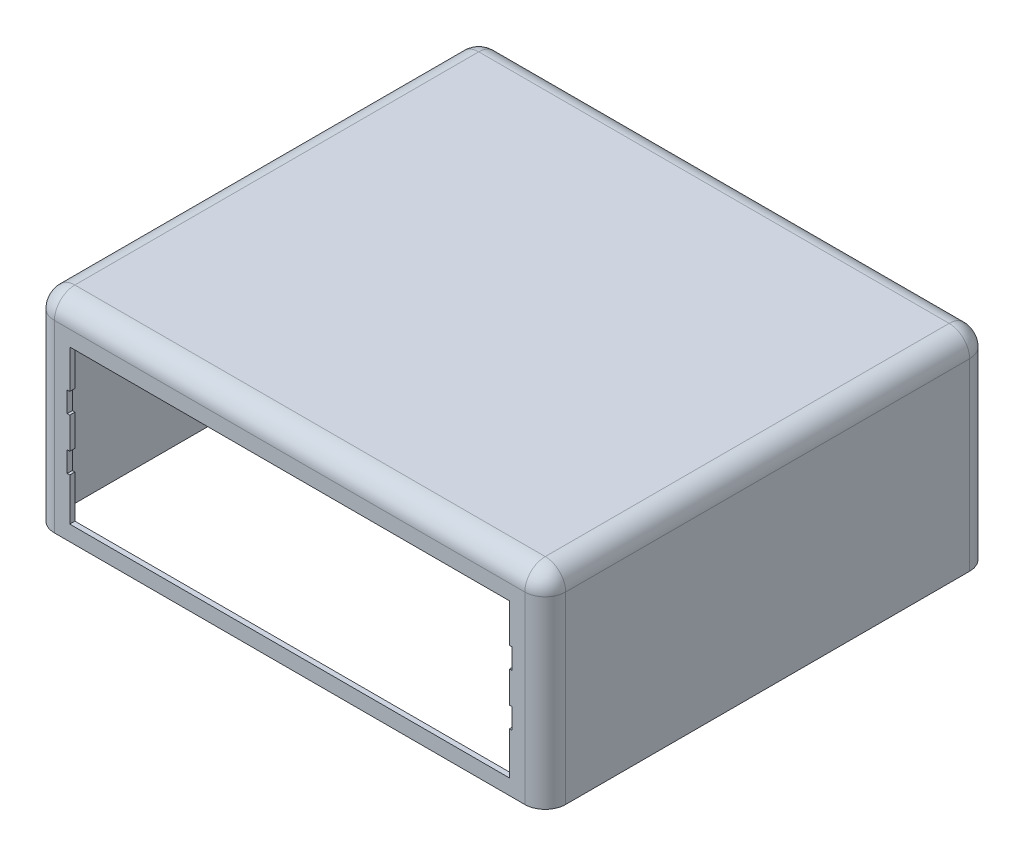
SolidWorks part; units mm, degrees
ref_plane "Front Plane" through (0, 0, 0) normal (0, 0, 1) x (1, 0, 0)
ref_plane "Top Plane" through (0, 0, 0) normal (0, 1, 0) x (1, 0, 0)
ref_plane "Right Plane" through (0, 0, 0) normal (1, 0, 0) x (0, 0, -1)
sketch "Sketch1" plane through (0, 0, 0) normal (0, 1, 0) x (1, 0, 0)
  line L1 (-1270, -1104.9) -> (1270, -1104.9)
  line L2 (-1270, -1104.9) -> (-1270, 1104.9)
  line L3 (-1270, 1104.9) -> (1270, 1104.9)
  line L4 (1270, -1104.9) -> (1270, 1104.9)
  line L5 (-1270, -1104.9) -> (1270, 1104.9) construction
  line L6 (-1270, 1104.9) -> (1270, -1104.9) construction
  point P0 (0, 0)
  dimension "D1" = 2209.8
  dimension "D2" = 2540
extrude "Boss-Extrude1" add sketch "Sketch1" along normal blind 1016
fillet "Fillet1" radius 101.6 8 edges at (1270, 508, 1104.9) (-1270, 508, 1104.9) (1270, 508, -1104.9) (-1270, 508, -1104.9) (0, 1016, 1104.9) (1270, 1016, 0) (0, 1016, -1104.9) (-1270, 1016, 0)
shell "Shell1" thickness 25.4
sketch "Sketch2" plane through (0, 0, 1104.9) normal (0, 0, 1) x (1, 0, 0)
  line L4 (-1092.2, 838.2) -> (-1092.2, 76.2)
  line L5 (-1092.2, 76.2) -> (1092.2, 76.2)
  line L6 (1092.2, 76.2) -> (1092.2, 838.2)
  line L7 (1092.2, 838.2) -> (-1092.2, 838.2)
extrude "Cut-Extrude1" cut sketch "Sketch2" against normal blind 101.6 contours L4 L5 L6 L7
sketch "Sketch4" plane through (0, 0, 1104.9) normal (0, 0, 1) x (1, 0, 0)
  line L0 (1092.2, 646.8673) -> (1092.2, 596.0673)
  line L1 (1092.2, 76.2) -> (1092.2, 838.2) construction
  line L2 (1092.2, 596.0673) -> (1092.2, 545.2673)
  line L3 (1092.2, 338.5566) -> (1092.2, 287.7566)
  line L4 (1092.2, 596.0673) -> (1092.2, 646.8673)
  line L5 (1092.2, 596.0673) -> (1092.2, 545.2673)
  line L6 (1092.2, 338.5566) -> (1092.2, 389.3566)
  line L7 (1092.2, 338.5566) -> (1092.2, 287.7566)
  line L8 (1092.2, 389.3566) -> (1092.2, 338.5566)
  line L9 (1092.2, 646.8673) -> (1104.9, 646.8673)
  line L10 (1104.9, 646.8673) -> (1104.9, 545.2673)
  line L11 (1104.9, 545.2673) -> (1092.2, 545.2673)
  line L12 (1092.2, 389.3566) -> (1104.9, 389.3566)
  line L13 (1104.9, 389.3566) -> (1104.9, 287.7566)
  line L14 (1104.9, 287.7566) -> (1092.2, 287.7566)
  line L15 (1092.2, 287.7566) -> (1092.2, 389.3566)
  line L16 (1092.2, 545.2673) -> (1092.2, 646.8673)
  line L17 (0, -558.8) -> (0, 558.8) construction
  line L18 (-1092.2, 389.3566) -> (-1104.9, 389.3566)
  line L19 (-1104.9, 287.7566) -> (-1092.2, 287.7566)
  line L20 (-1104.9, 389.3566) -> (-1104.9, 287.7566)
  line L21 (-1092.2, 338.5566) -> (-1092.2, 287.7566)
  line L22 (-1092.2, 338.5566) -> (-1092.2, 389.3566)
  line L23 (-1092.2, 646.8673) -> (-1104.9, 646.8673)
  line L24 (-1104.9, 545.2673) -> (-1092.2, 545.2673)
  line L25 (-1092.2, 596.0673) -> (-1092.2, 545.2673)
  line L26 (-1104.9, 646.8673) -> (-1104.9, 545.2673)
  line L27 (-1092.2, 646.8673) -> (-1092.2, 596.0673)
  point P0 (1098.55, 646.8673)
  line M11 (-1092.2, 76.2) -> (-1092.2, 838.2)
  line M13 (1092.2, 838.2) -> (1092.2, 76.2)
  dimension "D1" = 50.8
  dimension "D2" = 101.6
  dimension "D3" = 12.7
  dimension "D4" = 12.7
extrude "Cut-Extrude2" cut sketch "Sketch4" against normal blind 25.4 contours L18 L20 L19 M11 | L11 L10 L9 M13 | L14 L13 L12 M13 | L25 L24 L26 L23 L27
